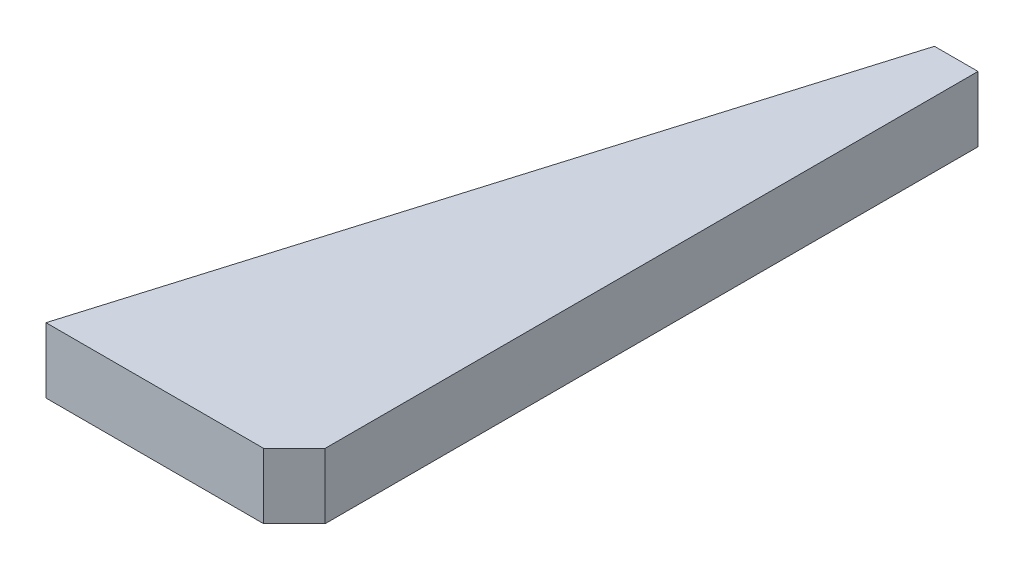
SolidWorks part; units mm, degrees
ref_plane "Front Plane" through (0, 0, 0) normal (0, 0, 1) x (1, 0, 0)
ref_plane "Top Plane" through (0, 0, 0) normal (0, 1, 0) x (1, 0, 0)
ref_plane "Right Plane" through (0, 0, 0) normal (1, 0, 0) x (0, 0, -1)
sketch "Sketch1" plane through (0, 0, 0) normal (0, 1, 0) x (1, 0, 0)
  line L0 (0, 0) -> (0, -150)
  line L1 (0, -150) -> (-7.0711, -157.0711)
  line L2 (-7.0711, -157.0711) -> (-57.0711, -157.0711)
  line L3 (0, 0) -> (-10, 0)
  line L4 (-10, 0) -> (-57.0711, -157.0711)
extrude "Boss-Extrude1" add sketch "Sketch1" along normal blind 15
